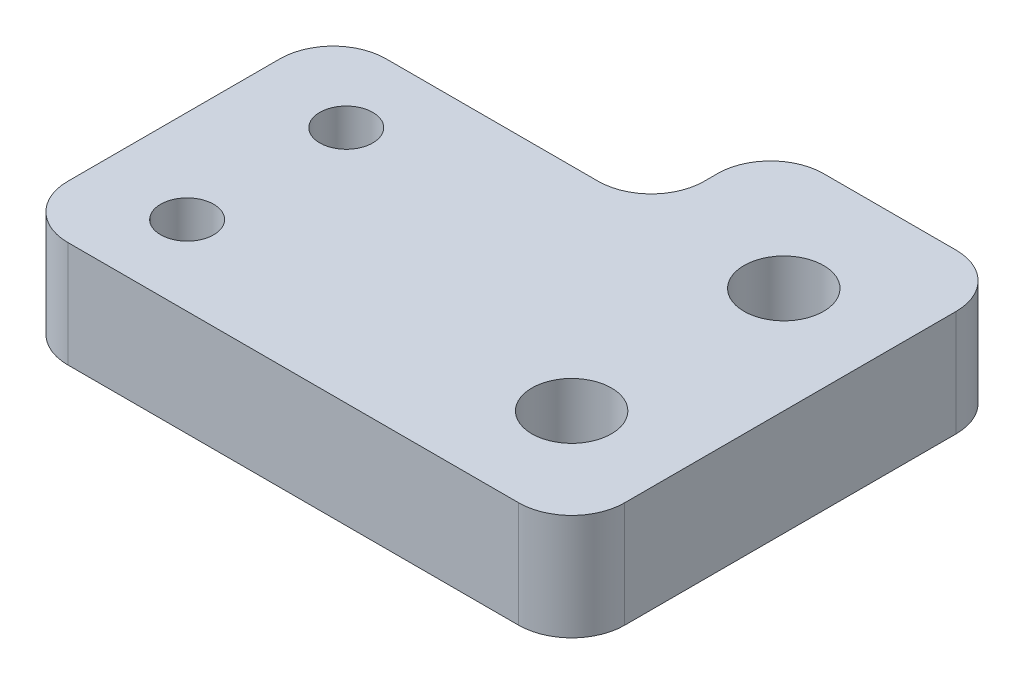
SolidWorks part; units mm, degrees
material "Thornel Mat VMA"
ref_plane "前视基准面" through (0, 0, 0) normal (0, 0, 1) x (1, 0, 0)
ref_plane "上视基准面" through (0, 0, 0) normal (0, 1, 0) x (1, 0, 0)
ref_plane "右视基准面" through (0, 0, 0) normal (1, 0, 0) x (0, 0, -1)
other "Configuration Table"
sketch "草图1" plane through (0, 0, 0) normal (0, 1, 0) x (1, 0, 0)
  line L0 (0, 0) -> (0, 16.3617) construction
  line L1 (-14.5, -8.5) -> (14.5, -8.5)
  line L2 (-14.5, -8.5) -> (-14.5, 8.5)
  line L3 (-14.5, 8.5) -> (14.5, 8.5)
  line L4 (14.5, -8.5) -> (14.5, 8.5)
  line L5 (-14.5, -8.5) -> (14.5, 8.5) construction
  line L6 (-14.5, 8.5) -> (14.5, -8.5) construction
  line L7 (0, 0) -> (24.482, 0) construction
  line L8 (-14.5, 3.5) -> (-2.5, 3.5)
  line L9 (-2.5, 3.5) -> (-2.5, 8.5)
  circle A0 centre (2.5, 3.5) radius 1.5
  circle A1 centre (2.5, -4.5) radius 1.5
  circle A2 centre (-11, 0.5) radius 1
  circle A3 centre (-11, -5.5) radius 1
  point P0 (0, 0)
  dimension "D1" = 3
  dimension "D2" = 3
  dimension "D5" = 8
  dimension "D6" = 12
  dimension "D7" = 12
  dimension "D8" = 3.5
  dimension "D9" = 2
  dimension "D11" = 9
  dimension "D14" = 2
  dimension "D15" = 11
  dimension "D3" = 29
  dimension "D4" = 17
  dimension "D10" = 11
  dimension "D12" = 12
  dimension "D13" = 5
  dimension "D16" = 3
extrude "凸台-拉伸1" add sketch "草图1" along normal blind 4
sketch "草图2" plane through (0, 4, 0) normal (0, 1, 0) x (1, 0, 0)
  line L0 (14.5, 8.5) -> (6.5, 8.5)
  line L2 (6.5, 8.5) -> (6.5, -8.5)
  line L3 (-14.5, -8.5) -> (14.5, -8.5) construction
  line L4 (6.5, -8.5) -> (14.5, -8.5)
  line L5 (14.5, -8.5) -> (14.5, 8.5)
  line L6 (6.5, 8.5) -> (-2.5, 8.5)
  line L7 (-2.5, 8.5) -> (14.5, 8.5) construction
  line L8 (-2.5, 8.5) -> (-2.5, 8)
  line L9 (-2.5, 3.5) -> (-2.5, 8.5) construction
  line L10 (-2.5, 8) -> (6.5, 8)
  line M9 (-2.5, 8.5) -> (-2.5, 3.5)
  line M12 (-14.5, -8.5) -> (14.5, -8.5)
  line M13 (14.5, -8.5) -> (14.5, 8.5)
  line M14 (14.5, 8.5) -> (-2.5, 8.5)
  dimension "D1" = 8
  dimension "D2" = 0.5
extrude "切除-拉伸1" cut sketch "草图2" against normal blind 10 contours L10 L2 M9 M14 | L2 M14 M12 M13
fillet "圆角1" radius 2 6 edges at (-14.5, 2, 8.5) (-14.5, 2, -3.5) (-2.5, 2, -3.5) (6.5, 2, 8.5) (6.5, 2, -8) (-2.5, 2, -8)
